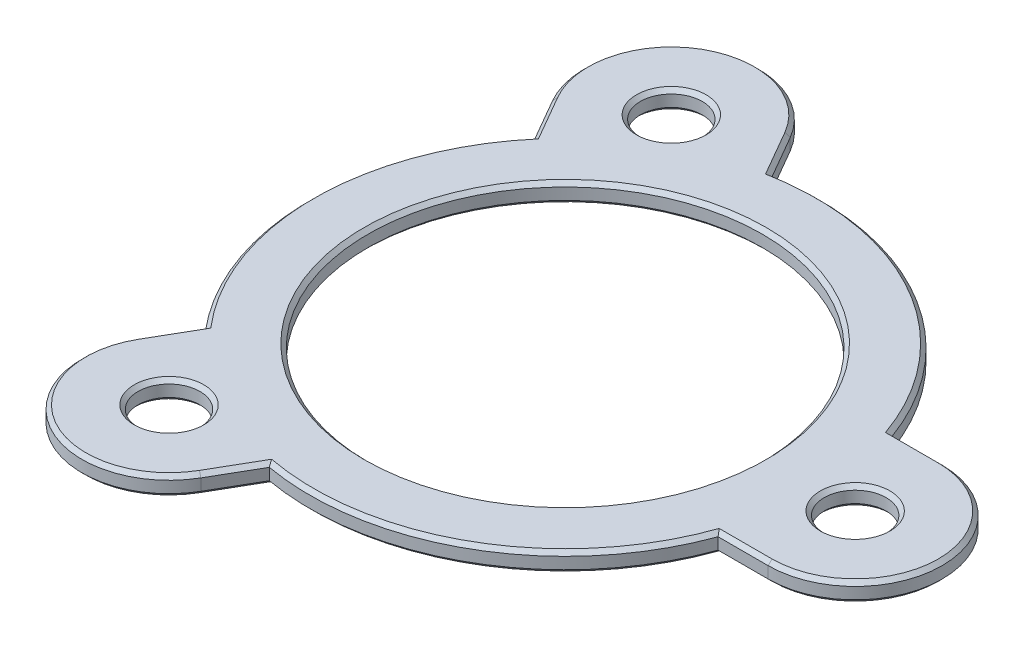
SolidWorks part; units mm, degrees
ref_plane "前视基准面" through (0, 0, 0) normal (0, 0, 1) x (1, 0, 0)
ref_plane "上视基准面" through (0, 0, 0) normal (0, 1, 0) x (1, 0, 0)
ref_plane "右视基准面" through (0, 0, 0) normal (1, 0, 0) x (0, 0, -1)
sketch "草图1" plane through (0, 0, 0) normal (0, 1, 0) x (1, 0, 0)
  line L0 (-10.1017, 8.4967) -> (-11.3971, 10.7404)
  line L1 (-2.3075, 12.9967) -> (-3.6029, 15.2404)
  line L2 (12.4093, -4.5) -> (15, -4.5)
  line L3 (12.4093, 4.5) -> (15, 4.5)
  line L4 (-10.1017, -8.4967) -> (-11.3971, -10.7404)
  line L5 (-2.3075, -12.9967) -> (-3.6029, -15.2404)
  line L16 (0, 0) -> (15, 0) construction
  line L17 (0, 0) -> (-7.5, -12.9904) construction
  line L18 (0, 0) -> (-7.5, 12.9904) construction
  circle A15 centre (0, 0) radius 10.2
  circle A18 centre (15, 0) radius 1.6
  circle A19 centre (-7.5, -12.9904) radius 1.6
  circle A20 centre (-7.5, 12.9904) radius 1.6
  circle A21 centre (0, 0) radius 13.2
  circle A22 centre (-7.5, 12.9904) radius 4.5
  circle A23 centre (15, 0) radius 4.5
  circle A24 centre (-7.5, -12.9904) radius 4.5
  point P8 (0, 0)
  point P22 (0, 0)
  point P46 (0, 0)
  dimension "D4" = 9
  dimension "D9" = 20.4
  dimension "D2" = 26.4
  dimension "D3" = 3.2
  dimension "D8" = 15
  dimension "D13" = 3
  dimension "D5" = 3
  dimension "D6" = 3
extrude "凸台-拉伸1" add sketch "草图1" along normal blind 1 contours A24 A21 A23 A22 A15 | A21 A23 | A23 A21 A18 | A23 A21 L2 | A23 L3 A21 | A24 A21 L4 | A24 L5 A21 | A21 A24 | A24 A21 A19 | A22 A21 L1 | A22 L0 A21 | A21 A22 | A21 A22 A20
chamfer "倒角1" distance 0.2 angle 45 32 edges at (15, 0, 1.6) (-7.5, 0, 14.5904) (-7.5, 0, -11.3904) (0, 0, 10.2) (19.5, 0, 0) (13.7046, 0, -4.5) (6.6, 0, -11.4315) (-2.9552, 0, -14.1186) (-9.75, 0, -16.8875) (-10.7494, 0, -9.6186) (-13.2, 0, 0) (-10.7494, 0, 9.6186) (-9.75, 0, 16.8875) (-2.9552, 0, 14.1186) (6.6, 0, 11.4315) (13.7046, 0, 4.5) (15, 1, 1.6) (-7.5, 1, 14.5904) (-7.5, 1, -11.3904) (0, 1, 10.2) (6.6, 1, 11.4315) (-2.9552, 1, 14.1186) (-9.75, 1, 16.8875) (-10.7494, 1, 9.6186) (-13.2, 1, 0) (-10.7494, 1, -9.6186) (-9.75, 1, -16.8875) (-2.9552, 1, -14.1186) (6.6, 1, -11.4315) (13.7046, 1, -4.5) (19.5, 1, 0) (13.7046, 1, 4.5)
equation "\"3。2\"=10"
